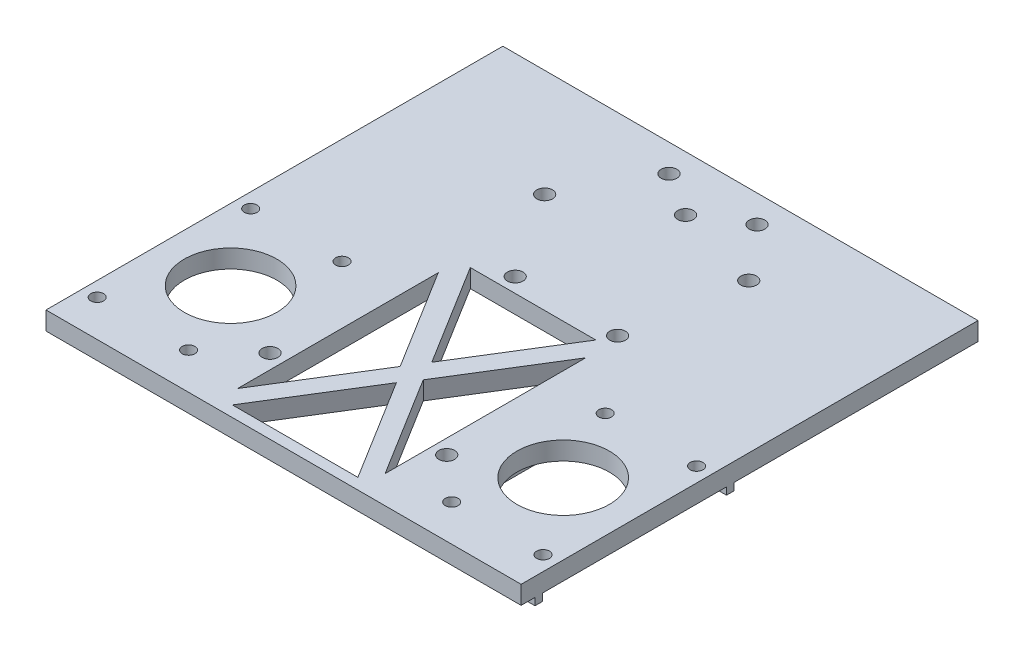
SolidWorks part; units mm, degrees
ref_plane "Front Plane" through (0, 0, 0) normal (0, 0, 1) x (1, 0, 0)
ref_plane "Top Plane" through (0, 0, 0) normal (0, 1, 0) x (1, 0, 0)
ref_plane "Right Plane" through (0, 0, 0) normal (1, 0, 0) x (0, 0, -1)
sketch "Sketch1" plane through (0, 0, 0) normal (0, 1, 0) x (1, 0, 0)
  line L1 (-65, 62.5) -> (65, 62.5)
  line L2 (-65, 62.5) -> (-65, -62.5)
  line L3 (-65, -62.5) -> (65, -62.5)
  line L4 (65, 62.5) -> (65, -62.5)
  line L5 (-65, 62.5) -> (65, -62.5) construction
  line L6 (-65, -62.5) -> (65, 62.5) construction
  point P0 (0, 0)
  dimension "D1" = 130
  dimension "D2" = 125
extrude "Boss-Extrude1" add sketch "Sketch1" along normal blind 5
sketch "Sketch2" plane through (0, 5, 0) normal (0, 1, 0) x (1, 0, 0)
  line L1 (-65, -62.5) -> (65, -62.5) construction
  line L2 (-65, 62.5) -> (-65, -62.5) construction
  circle A0 centre (-61, -52.5) radius 1.75
  circle A1 centre (-36, -52.5) radius 1.75
  circle A2 centre (-36, -10.5) radius 1.75
  circle A3 centre (-61, -10.5) radius 1.75
  circle A4 centre (-45.5, -31.5) radius 12.65
  dimension "D2" = 25.3
  dimension "D7" = 3.5
  dimension "D8" = 3.5
  dimension "D9" = 3.5
  dimension "D10" = 3.5
  dimension "D1" = 19.5
  dimension "D3" = 31
  dimension "D4" = 4
  dimension "D5" = 10
  dimension "D6" = 10
  dimension "D11" = 4
  dimension "D12" = 42
  dimension "D13" = 42
  dimension "D14" = 25
  dimension "D15" = 25
extrude "Cut-Extrude1" cut sketch "Sketch2" against normal blind 10
ref_plane "Plane1" through (0, 0, 0) normal (-1, 0, 0) x (0, 0, 1)
ref_plane "Plane2" through (0, 0, 0) normal (0, 0, 1) x (1, 0, 0)
mirror "Mirror3" about plane through (0, 0, 0) normal (-1, 0, 0) of "Cut-Extrude1"
sketch "Sketch3" plane through (0, 5, 0) normal (0, 1, 0) x (1, 0, 0)
  line L0 (-65, -62.5) -> (65, -62.5) construction
  line L1 (-65, 62.5) -> (-65, -62.5) construction
  line L2 (65, -62.5) -> (65, 62.5) construction
  line L3 (65, 62.5) -> (-65, 62.5) construction
  circle A0 centre (-24.17, -42.03) radius 2.15
  circle A1 centre (24.17, -42.03) radius 2.15
  circle A2 centre (-8.73, 9.6) radius 2.15
  circle A3 centre (19.29, 9.6) radius 2.15
  circle A4 centre (-24.17, 33.11) radius 2.15
  circle A5 centre (24.17, 40.6) radius 2.15
  dimension "D1" = 4.3
  dimension "D6" = 4.3
  dimension "D7" = 4.3
  dimension "D10" = 4.3
  dimension "D11" = 4.3
  dimension "D12" = 4.3
  dimension "D2" = 20.47
  dimension "D3" = 40.83
  dimension "D4" = 20.47
  dimension "D5" = 40.83
  dimension "D8" = 72.1
  dimension "D9" = 56.27
  dimension "D13" = 45.71
  dimension "D14" = 72.1
  dimension "D15" = 29.39
  dimension "D16" = 21.9
  dimension "D17" = 40.83
extrude "Cut-Extrude2" cut sketch "Sketch3" against normal blind 10
sketch "Sketch4" plane through (0, 5, 0) normal (0, 1, 0) x (1, 0, 0)
  line L0 (0, 62.5) -> (0, 47.5) construction
  line L1 (65, 62.5) -> (-65, 62.5) construction
  line L2 (-12.0498, 55) -> (12.0498, 55) construction
  circle A0 centre (0, 47.5) radius 2.15
  circle A1 centre (12.0498, 55) radius 2.15
  circle A2 centre (-12.0498, 55) radius 2.15
  point P9 (0, 55)
  dimension "D2" = 4.3
  dimension "D3" = 4.3
  dimension "D4" = 4.3
  dimension "D1" = 15
  dimension "D5" = 24.0996
extrude "Cut-Extrude3" cut sketch "Sketch4" against normal blind 10
sketch "Sketch5" plane through (0, 0, 0) normal (0, -1, 0) x (1, 0, 0)
  line L0 (-58.15, 31.5) -> (-65, 31.5) construction
  line L1 (-65, -62.5) -> (-65, 62.5) construction
  line L2 (-65, 56.7) -> (-65, 6.3) construction
  line L3 (-65, 56.7) -> (-65, 58.7)
  line L4 (-65, 56.7) -> (-31.6, 56.7)
  line L5 (-65, 56.7) -> (-65, 6.3)
  line L6 (-65, 6.3) -> (-31.6, 6.3)
  line L7 (-31.6, 56.7) -> (-31.6, 6.3)
  line L8 (-65, 58.7) -> (-29.6, 58.7)
  line L9 (-29.6, 58.7) -> (-29.6, 4.3)
  line L10 (-29.6, 4.3) -> (-65, 4.3)
  line L11 (-65, 4.3) -> (-65, 6.3)
  circle A0 centre (-45.5, 31.5) radius 12.65 construction
  point P10 (-65, 31.5)
  line M37 (-65, 62.5) -> (-65, -62.5)
  dimension "D1" = 50.4
  dimension "D2" = 33.4
  dimension "D3" = 2
  dimension "D4" = 2
  dimension "D5" = 2
extrude "Boss-Extrude2" add sketch "Sketch5" along normal blind 2 contours L10 L9 L8 L4 L7 L6 M37
mirror "Mirror6" about plane through (0, 0, 0) normal (-1, 0, 0) of "Boss-Extrude2"
sketch "Sketch6" plane through (0, 0, 0) normal (0, -1, 0) x (1, 0, 0)
  circle A0 centre (-8.73, -9.6) radius 2.65
  circle A1 centre (19.29, -9.6) radius 2.65
  circle A2 centre (-24.17, -33.11) radius 2.65
  circle A3 centre (24.17, -40.6) radius 2.65
  circle A4 centre (0, -47.5) radius 2.65
  circle A5 centre (-12.0498, -55) radius 2.65
  circle A6 centre (12.0498, -55) radius 2.65
  circle A7 centre (-61, 10.5) radius 2.65
  circle A8 centre (-36, 10.5) radius 2.65
  circle A9 centre (-36, 52.5) radius 2.65
  circle A10 centre (-61, 52.5) radius 2.65
  circle A11 centre (36, 52.5) radius 2.65
  circle A12 centre (36, 10.5) radius 2.65
  circle A13 centre (61, 10.5) radius 2.65
  circle A14 centre (61, 52.5) radius 2.65
  circle A15 centre (-24.17, 42.03) radius 2.65
  circle A16 centre (24.17, 42.03) radius 2.65
  dimension "D1" = 5.3
  dimension "D2" = 5.3
  dimension "D3" = 5.3
  dimension "D4" = 5.3
  dimension "D5" = 5.3
  dimension "D6" = 5.3
  dimension "D7" = 5.3
  dimension "D8" = 5.3
  dimension "D9" = 5.3
  dimension "D10" = 5.3
  dimension "D11" = 5.3
  dimension "D12" = 5.3
  dimension "D13" = 5.3
  dimension "D14" = 5.3
  dimension "D15" = 5.3
  dimension "D16" = 5.3
  dimension "D17" = 5.3
extrude "Cut-Extrude5" cut sketch "Sketch6" against normal blind 0.5
sketch "Sketch7" plane through (0, 5, 0) normal (0, 1, 0) x (1, 0, 0)
  line L0 (-65, -62.5) -> (65, -62.5) construction
  line L1 (-20.17, 5.6) -> (20.17, 5.6)
  line L2 (-20.17, 5.6) -> (-20.17, -59.5)
  line L3 (-20.17, -59.5) -> (20.17, -59.5)
  line L4 (20.17, 5.6) -> (20.17, -59.5)
  line L5 (-20.17, 5.6) -> (20.17, -59.5) construction
  line L6 (20.17, 5.6) -> (-20.17, -59.5) construction
  line L7 (-17.0037, 5.6) -> (0.1646, -22.106)
  line L8 (0.1646, -22.106) -> (17.333, 5.6)
  line L9 (20.17, 0) -> (3.1637, -27.4444)
  line L10 (3.1637, -27.4444) -> (20.17, -54.8888)
  line L11 (17.333, -59.5) -> (0.1646, -31.794)
  line L12 (0.1646, -31.794) -> (-17.0037, -59.5)
  line L13 (-20.17, -54.8888) -> (-3.1637, -27.4444)
  line L14 (-3.1637, -27.4444) -> (-20.17, 0)
  circle A0 centre (-24.17, -42.03) radius 2.15 construction
  circle A1 centre (24.17, -42.03) radius 2.15 construction
  circle A2 centre (-8.73, 9.6) radius 2.15 construction
  dimension "D1" = 4
  dimension "D4" = 4
  dimension "D2" = 4
  dimension "D3" = 3
extrude "Cut-Extrude7" cut sketch "Sketch7" against normal through all contours L13 L14 L2 | L7 L8 L1 | L9 L10 L4 | L11 L12 L3
